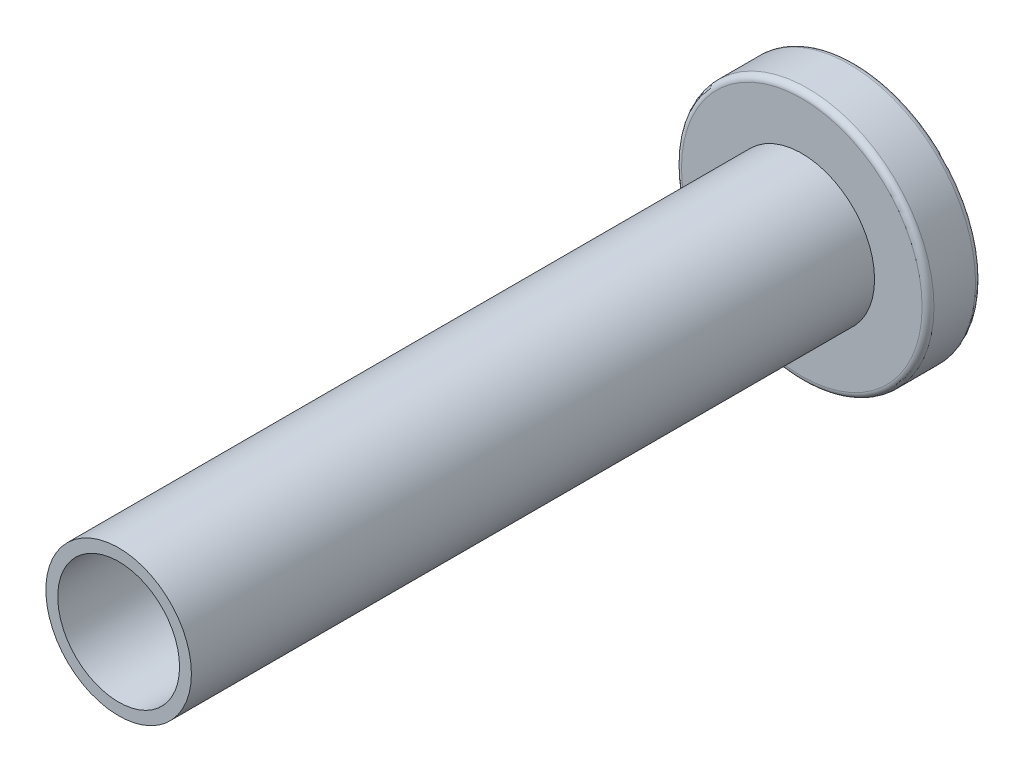
SolidWorks part; units mm, degrees
material "AISI 304"
ref_plane "前视基准面" through (0, 0, 0) normal (0, 0, 1) x (1, 0, 0)
ref_plane "上视基准面" through (0, 0, 0) normal (0, 1, 0) x (1, 0, 0)
ref_plane "右视基准面" through (0, 0, 0) normal (1, 0, 0) x (0, 0, -1)
other "Configuration Table"
sketch "草图1" plane through (0, 0, 0) normal (0, 0, 1) x (1, 0, 0)
  circle A0 centre (0, 0) radius 4.25
  dimension "D1" = 8.5
extrude "凸台-拉伸1" add sketch "草图1" along normal blind 1.8
sketch "草图2" plane through (0, 0, 1.8) normal (0, 0, 1) x (1, 0, 0)
  circle A0 centre (0, 0) radius 2.45
  circle A1 centre (0, 0) radius 2.05
  dimension "D1" = 4.9
  dimension "D2" = 4.1
extrude "凸台-拉伸2" add sketch "草图2" along normal blind 23
fillet "圆角1" radius 0.2 2 edges at (4.25, 0, 0) (4.25, 0, 1.8)
sketch "草图3" plane through (0, 0, 0) normal (0, 0, -1) x (-1, 0, 0)
  line L0 (0, 0) -> (1.4434, 0) construction
  line L1 (1.4434, 0) -> (0.7217, 1.25)
  line L2 (0.7217, 1.25) -> (-0.7217, 1.25)
  line L3 (-0.7217, 1.25) -> (-1.4434, 0)
  line L4 (-1.4434, 0) -> (-0.7217, -1.25)
  line L5 (-0.7217, -1.25) -> (0.7217, -1.25)
  line L6 (0.7217, -1.25) -> (1.4434, 0)
  circle A0 centre (0, 0) radius 1.25 construction
  dimension "D1" = 2.5
extrude "切除-拉伸1" cut sketch "草图3" against normal blind 1
